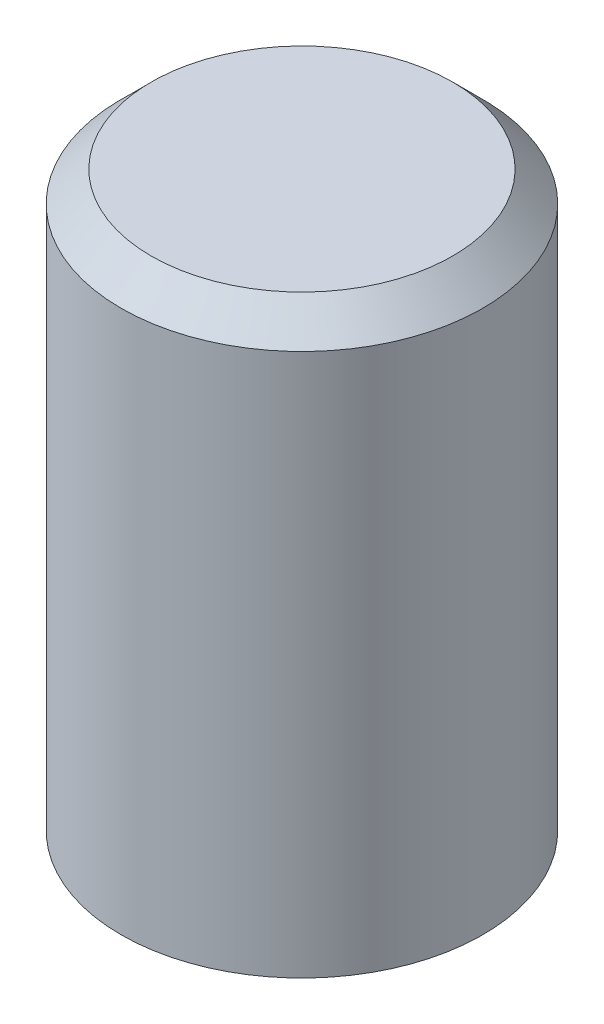
SolidWorks part; units mm, degrees
ref_plane "Front Plane" through (0, 0, 0) normal (0, 0, 1) x (1, 0, 0)
ref_plane "Top Plane" through (0, 0, 0) normal (0, 1, 0) x (1, 0, 0)
ref_plane "Right Plane" through (0, 0, 0) normal (1, 0, 0) x (0, 0, -1)
sketch "Skizze1" plane through (0, 0, 0) normal (0, 1, 0) x (1, 0, 0)
  circle A0 centre (0, 0) radius 3
extrude "Aufsatz-Linear austragen1" add sketch "Skizze1" along normal blind 9.5
chamfer "Fase1" distance 0.5 angle 45 1 edges at (0, 9.5, 3)
